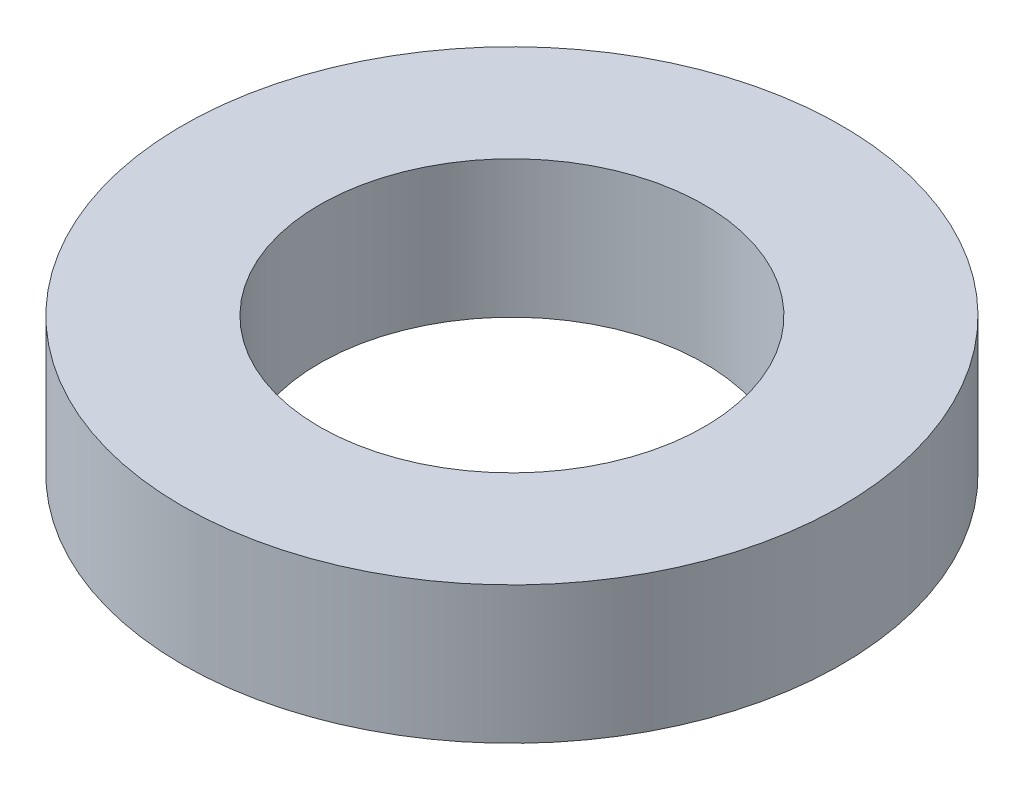
SolidWorks part; units mm, degrees
ref_plane "Front Plane" through (0, 0, 0) normal (0, 0, 1) x (1, 0, 0)
ref_plane "Top Plane" through (0, 0, 0) normal (0, 1, 0) x (1, 0, 0)
ref_plane "Right Plane" through (0, 0, 0) normal (1, 0, 0) x (0, 0, -1)
sketch "Sketch1" plane through (0, 0, 0) normal (0, 1, 0) x (1, 0, 0)
  circle A0 centre (0, 0) radius 14.02
  circle A1 centre (0, 0) radius 24.02
  dimension "D1" = 10
  dimension "D2" = 28.04
extrude "Boss-Extrude1" add sketch "Sketch1" along normal blind 10 contours A1 | A0
